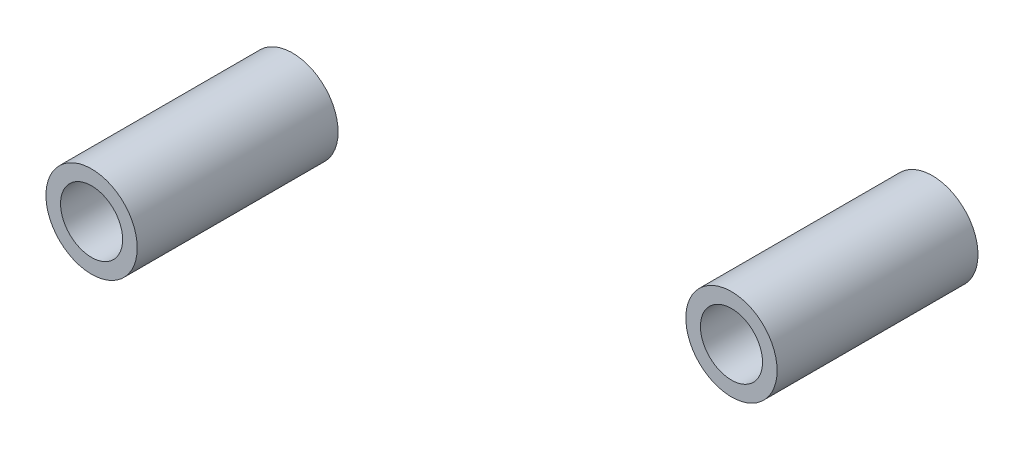
SolidWorks part; units mm, degrees
ref_plane "Front Plane" through (0, 0, 0) normal (0, 0, 1) x (1, 0, 0)
ref_plane "Top Plane" through (0, 0, 0) normal (0, 1, 0) x (1, 0, 0)
ref_plane "Right Plane" through (0, 0, 0) normal (1, 0, 0) x (0, 0, -1)
ref_plane "Plane1" through (0, 0, 347.5) normal (0, 0, 1) x (1, 0, 0)
sketch "Sketch1" plane through (0, 0, 347.5) normal (0, 0, 1) x (1, 0, 0)
  circle A0 centre (315.0909, 53.1249) radius 2.5
  circle A1 centre (315.0909, 53.1249) radius 1.7
extrude "Boss-Extrude1" add sketch "Sketch1" along normal blind 11
sketch "Sketch2" plane through (0, 0, 347.5) normal (0, 0, 1) x (1, 0, 0)
  circle A0 centre (280.0506, 41.4224) radius 2.5
  circle A1 centre (280.0506, 41.4224) radius 1.7
extrude "Boss-Extrude2" add sketch "Sketch2" along normal blind 11
